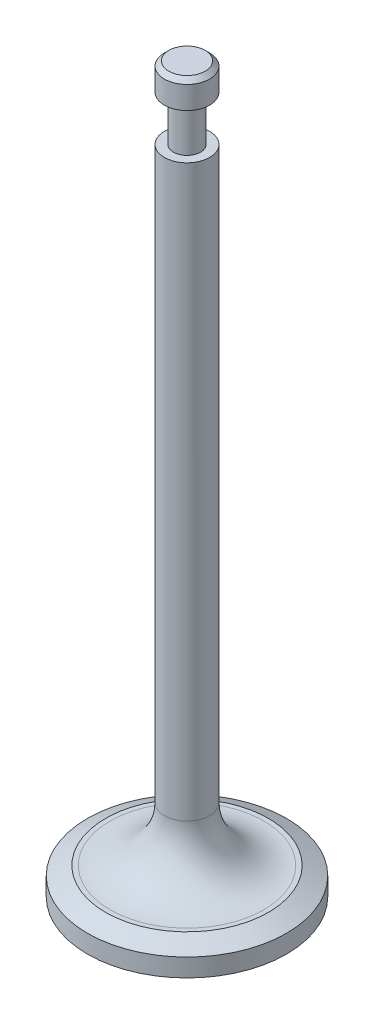
SolidWorks part; units mm, degrees
ref_plane "Front Plane" through (0, 0, 0) normal (0, 0, 1) x (1, 0, 0)
ref_plane "Top Plane" through (0, 0, 0) normal (0, 1, 0) x (1, 0, 0)
ref_plane "Right Plane" through (0, 0, 0) normal (1, 0, 0) x (0, 0, -1)
sketch "Sketch2" plane through (0, 0, 0) normal (0, 0, 1) x (1, 0, 0)
  line L0 (0, 0) -> (0, 80)
  line L1 (0, 80) -> (2.5, 80)
  line L2 (2.5, 80) -> (2.5, 77)
  line L3 (2.5, 77) -> (1.5, 77)
  line L4 (1.5, 77) -> (1.5, 72)
  line L5 (1.5, 72) -> (2.5, 72)
  line L6 (2.5, 72) -> (2.5, 3)
  line L7 (2.5, 3) -> (11, 3)
  line L8 (11, 3) -> (11, 0)
  line L9 (11, 0) -> (0, 0)
  dimension "D1" = 1
  dimension "D2" = 80
  dimension "D3" = 3
  dimension "D4" = 11
  dimension "D5" = 3
  dimension "D6" = 2.5
  dimension "D7" = 5
revolve "Revolve1" add sketch "Sketch2" angle 360 about L0
fillet "Fillet1" radius 6 1 edges at (0, 3, -2.5)
chamfer "Chamfer1" distance 0.5 angle 45 1 edges at (0, 80, -2.5)
chamfer "Chamfer2" distance 2 distance2 1 1 edges at (0, 3, -11)
